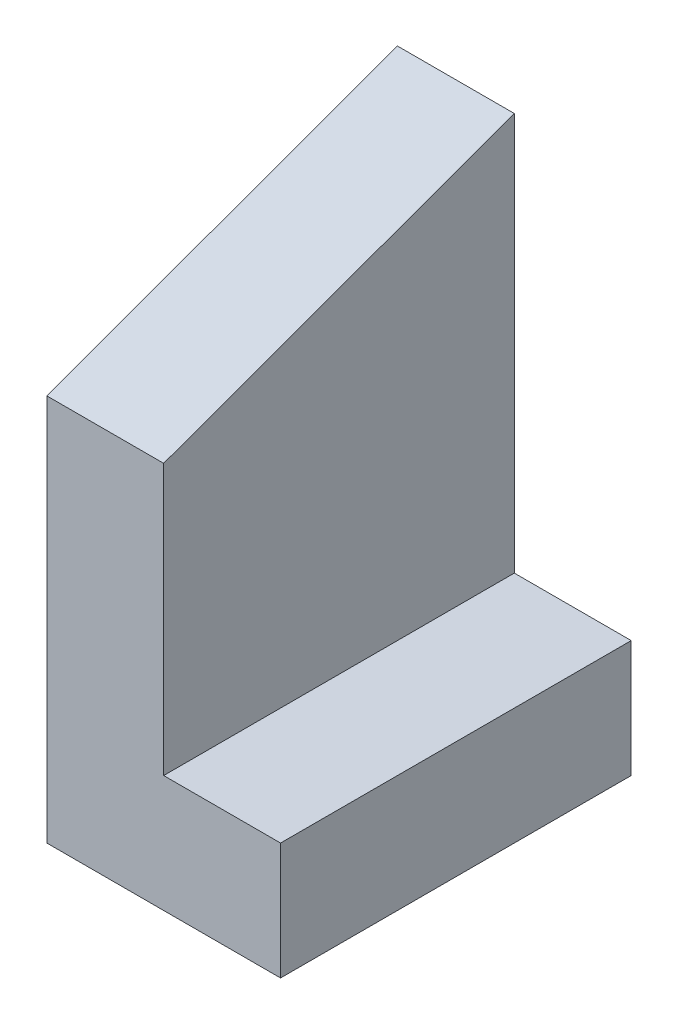
SolidWorks part; units mm, degrees
ref_plane "Front Plane" through (0, 0, 0) normal (0, 0, 1) x (1, 0, 0)
ref_plane "Top Plane" through (0, 0, 0) normal (0, 1, 0) x (1, 0, 0)
ref_plane "Right Plane" through (0, 0, 0) normal (1, 0, 0) x (0, 0, -1)
sketch "Sketch1" plane through (0, 0, 0) normal (0, 0, 1) x (1, 0, 0)
  line L0 (0, 0) -> (0, 25)
  line L1 (0, 0) -> (10, 0)
  line L2 (5, 5) -> (10, 5)
  line L3 (5, 5) -> (5, 25)
  line L4 (0, 25) -> (5, 25)
  line L5 (10, 5) -> (10, 0)
  dimension "D1" = 25
  dimension "D2" = 10
  dimension "D3" = 5
extrude "Boss-Extrude1" add sketch "Sketch1" along normal blind 15
sketch "Sketch2" plane through (5, 0, 0) normal (1, 0, 0) x (0, 0, -1)
  line L0 (-15, 16.5668) -> (0, 22.0263)
  line L1 (-15, 5) -> (-15, 25) construction
  line L2 (0, 5) -> (0, 25) construction
  line L3 (-25.0217, 13.9833) -> (11.6263, 27.3221) construction
  line L4 (11.7973, 26.8523) -> (-24.8507, 13.5135) construction
  line L5 (-15, 16.5668) -> (-25.2289, 33.944)
  line L6 (-25.2289, 33.944) -> (4.6201, 27.8701)
  line L7 (4.6201, 27.8701) -> (0, 22.0263)
  point P10 (-25.2289, 33.4119)
  dimension "D1" = 0.5
extrude "Cut-Extrude1" cut sketch "Sketch2" against normal blind 10
